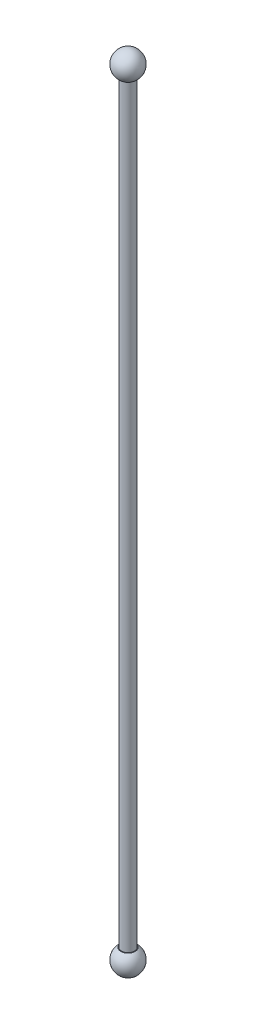
SolidWorks part; units mm, degrees
material "Hexcel AS4C (3000 волосков)"
ref_plane "Спереди" through (0, 0, 0) normal (0, 0, 1) x (1, 0, 0)
ref_plane "Сверху" through (0, 0, 0) normal (0, 1, 0) x (1, 0, 0)
ref_plane "Справа" through (0, 0, 0) normal (1, 0, 0) x (0, 0, -1)
sketch "Эскиз1" plane through (0, 0, 0) normal (0, 0, 1) x (1, 0, 0)
  line L0 (2, 175.35) -> (2, -175.35)
  line L1 (2, -175.35) -> (3, -175.35)
  line L2 (3, -175.35) -> (3, 175.35)
  line L3 (3, 175.35) -> (2, 175.35)
  line L4 (0, 0) -> (0, 226.7951) construction
  point P7 (2, 0)
  dimension "D1" = 350.7
  dimension "D2" = 4
  dimension "D3" = 1
revolve "Повернуть1" add sketch "Эскиз1" angle 360 about L4
sketch "Эскиз2" plane through (0, 0, 0) normal (0, 0, 1) x (1, 0, 0)
  line L2 (0, 175.35) -> (0, 186.35)
  line L5 (2, 175.35) -> (-2, 175.35) construction
  line L6 (3, 175.35) -> (-3, 175.35) construction
  line L7 (0, 175.35) -> (3.3166, 175.35)
  arc A2 (0, 186.35) -> (3.3166, 175.35) centre (0, 180.35) cw
  dimension "D1" = 6
  dimension "D2" = 11
revolve "Повернуть5" add sketch "Эскиз2" angle 360 about L2
mirror "Зеркальное отражение1" about plane through (0, 0, 0) normal (0, 1, 0) of "Повернуть5"
